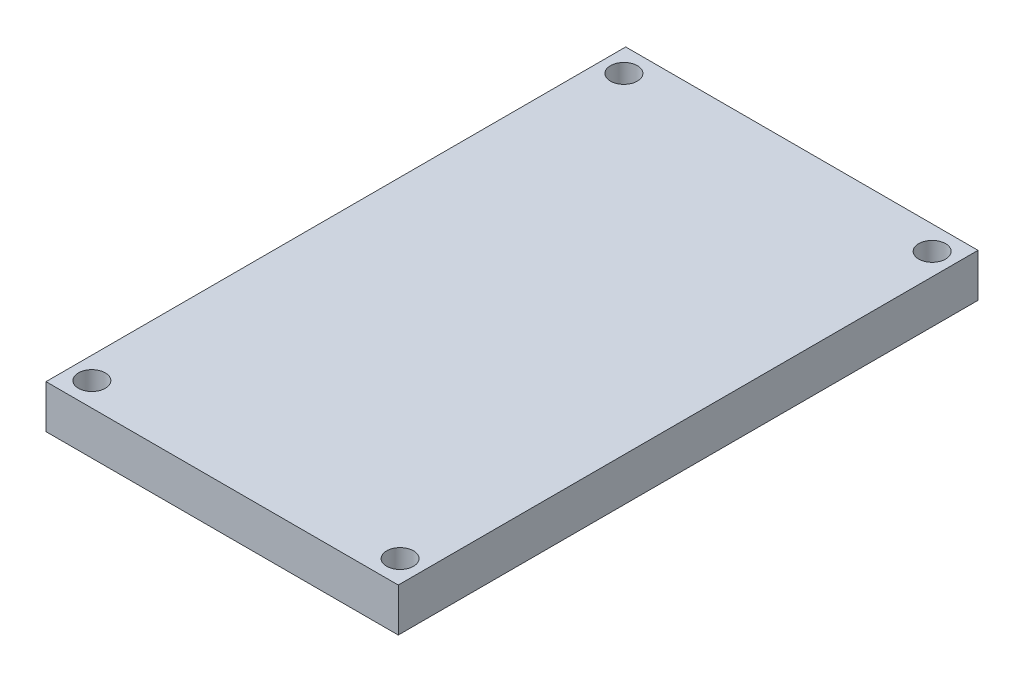
SolidWorks part; units mm, degrees
ref_plane "前视基准面" through (0, 0, 0) normal (0, 0, 1) x (1, 0, 0)
ref_plane "上视基准面" through (0, 0, 0) normal (0, 1, 0) x (1, 0, 0)
ref_plane "右视基准面" through (0, 0, 0) normal (1, 0, 0) x (0, 0, -1)
other "Configuration Table"
sketch "草图1" plane through (0, 0, 0) normal (0, 1, 0) x (1, 0, 0)
  line L0 (34.685, 0) -> (-34.685, 0) construction
  line L1 (-20.32, 33.44) -> (20.32, 33.44)
  line L2 (-20.32, 33.44) -> (-20.32, -33.44)
  line L3 (-20.32, -33.44) -> (20.32, -33.44)
  line L4 (20.32, 33.44) -> (20.32, -33.44)
  line L5 (-20.32, 33.44) -> (20.32, -33.44) construction
  line L6 (-20.32, -33.44) -> (20.32, 33.44) construction
  line L7 (0, 50.8212) -> (0, -50.8212) construction
  circle A0 centre (-17.78, 30.69) radius 1.55
  circle A1 centre (17.78, 30.69) radius 1.55
  circle A2 centre (17.78, -30.69) radius 1.55
  circle A3 centre (-17.78, -30.69) radius 1.55
  point P0 (0, 0)
  point P8 (0, 0)
  point P13 (0, 0)
  point P14 (0, 0)
  dimension "D3" = 3.1
  dimension "D1" = 40.64
  dimension "D2" = 66.88
  dimension "D4" = 2.54
  dimension "D5" = 2.75
extrude "凸台-拉伸1" add sketch "草图1" along normal blind 5
